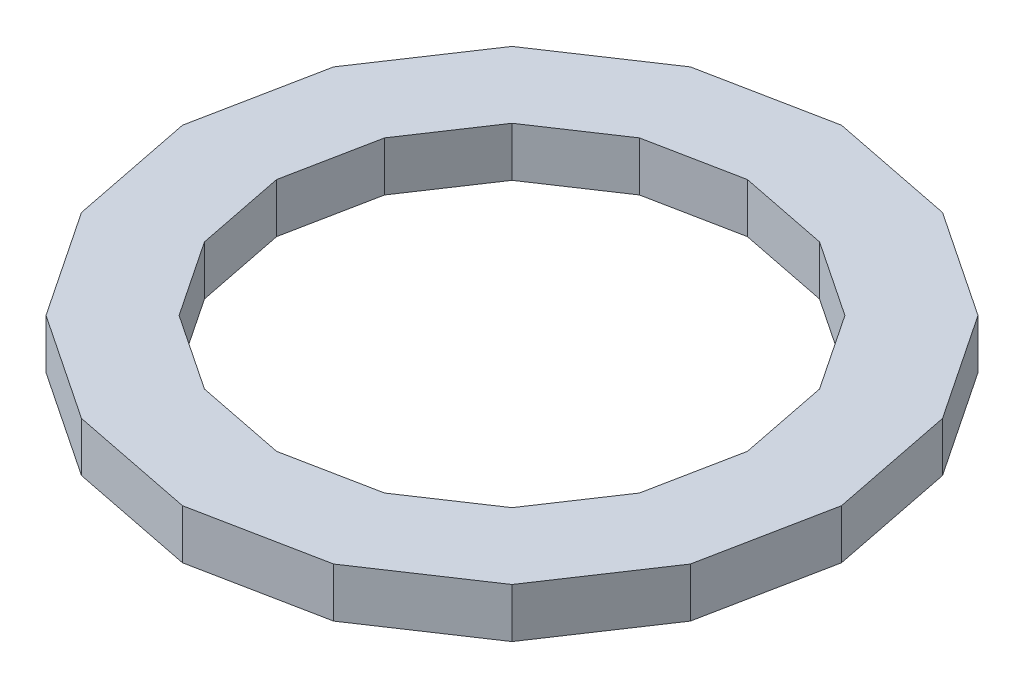
SolidWorks part; units mm, degrees
ref_plane "Front Plane" through (0, 0, 0) normal (0, 0, 1) x (1, 0, 0)
ref_plane "Top Plane" through (0, 0, 0) normal (0, 1, 0) x (1, 0, 0)
ref_plane "Right Plane" through (0, 0, 0) normal (1, 0, 0) x (0, 0, -1)
sketch "Sketch1" plane through (0, 0, 0) normal (0, 1, 0) x (1, 0, 0)
  line L1 (90.6845, 0) -> (83.7816, 34.7035)
  line L2 (83.7816, 34.7035) -> (64.1237, 64.1237)
  line L3 (64.1237, 64.1237) -> (34.7035, 83.7816)
  line L4 (34.7035, 83.7816) -> (0, 90.6845)
  line L5 (0, 90.6845) -> (-34.7035, 83.7816)
  line L6 (-34.7035, 83.7816) -> (-64.1237, 64.1237)
  line L7 (-64.1237, 64.1237) -> (-83.7816, 34.7035)
  line L8 (-83.7816, 34.7035) -> (-90.6845, 0)
  line L9 (-90.6845, 0) -> (-83.7816, -34.7035)
  line L10 (-83.7816, -34.7035) -> (-64.1237, -64.1237)
  line L11 (-64.1237, -64.1237) -> (-34.7035, -83.7816)
  line L12 (-34.7035, -83.7816) -> (0, -90.6845)
  line L13 (0, -90.6845) -> (34.7035, -83.7816)
  line L14 (34.7035, -83.7816) -> (64.1237, -64.1237)
  line L15 (64.1237, -64.1237) -> (83.7816, -34.7035)
  line L16 (83.7816, -34.7035) -> (90.6845, 0)
  line L17 (126.9412, 0) -> (117.2784, 48.5783)
  line L18 (117.2784, 48.5783) -> (89.761, 89.761)
  line L19 (89.761, 89.761) -> (48.5783, 117.2784)
  line L20 (48.5783, 117.2784) -> (0, 126.9412)
  line L21 (0, 126.9412) -> (-48.5783, 117.2784)
  line L22 (-48.5783, 117.2784) -> (-89.761, 89.761)
  line L23 (-89.761, 89.761) -> (-117.2784, 48.5783)
  line L24 (-117.2784, 48.5783) -> (-126.9412, 0)
  line L25 (-126.9412, 0) -> (-117.2784, -48.5783)
  line L26 (-117.2784, -48.5783) -> (-89.761, -89.761)
  line L27 (-89.761, -89.761) -> (-48.5783, -117.2784)
  line L28 (-48.5783, -117.2784) -> (0, -126.9412)
  line L29 (0, -126.9412) -> (48.5783, -117.2784)
  line L30 (48.5783, -117.2784) -> (89.761, -89.761)
  line L31 (89.761, -89.761) -> (117.2784, -48.5783)
  line L32 (117.2784, -48.5783) -> (126.9412, 0)
  circle A0 centre (0, 0) radius 88.9421 construction
  circle A1 centre (0, 0) radius 124.5021 construction
  dimension "D1" = 49.53
  dimension "D2" = 35.56
extrude "Boss-Extrude1" add sketch "Sketch1" along normal blind 19.05
